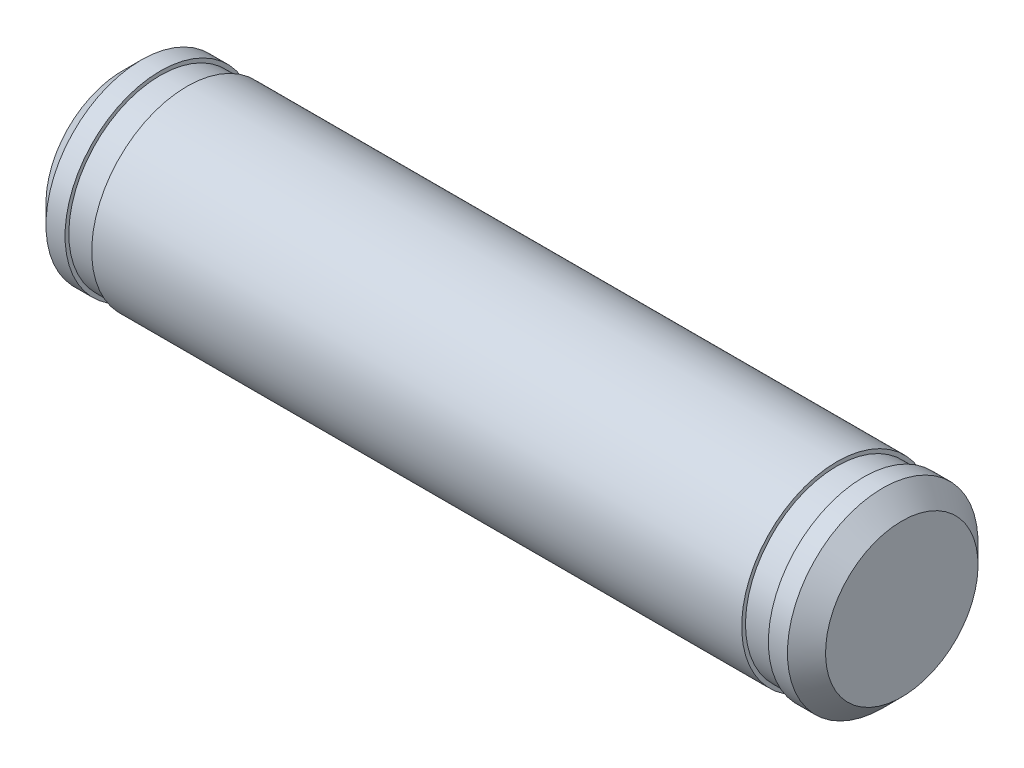
SolidWorks part; units mm, degrees
ref_plane "前视基准面" through (0, 0, 0) normal (0, 0, 1) x (1, 0, 0)
ref_plane "上视基准面" through (0, 0, 0) normal (0, 1, 0) x (1, 0, 0)
ref_plane "右视基准面" through (0, 0, 0) normal (1, 0, 0) x (0, 0, -1)
other "Configuration Table"
sketch "草图1" plane through (0, 0, 0) normal (0, 0, 1) x (1, 0, 0)
  line L0 (-0.2254, 0) -> (10.225, 0) construction
  line L1 (10.225, 0) -> (10.225, 2.5)
  line L2 (10.225, 2.5) -> (9.225, 2.5)
  line L3 (9.225, 2.5) -> (9.225, 2.4)
  line L4 (9.225, 2.4) -> (8.525, 2.4)
  line L5 (8.525, 2.4) -> (8.525, 2.5)
  line L6 (8.525, 2.5) -> (-8.525, 2.5)
  line L7 (0, 2.5) -> (0, 0) construction
  line L8 (0.2254, 0) -> (-10.225, 0) construction
  line L9 (-10.225, 0) -> (-10.225, 2.5)
  line L10 (-8.525, 2.4) -> (-8.525, 2.5)
  line L11 (-9.225, 2.4) -> (-8.525, 2.4)
  line L12 (-9.225, 2.5) -> (-9.225, 2.4)
  line L13 (-10.225, 2.5) -> (-9.225, 2.5)
  line L14 (10.225, 0) -> (-10.225, 0)
  line L15 (8.625, 2.4) -> (8.625, 0) construction
  line L16 (-8.625, 2.4) -> (-8.625, 0) construction
  dimension "D1" = 5
  dimension "D2" = 4.8
  dimension "D3" = 0.7
  dimension "D4" = 1
  dimension "D5" = 0.6
  dimension "D6" = 17.25
revolve "旋转1" add sketch "草图1" angle 360 about L14
chamfer "倒角1" distance 0.5 angle 45 2 edges at (10.225, 2.5, 0) (-10.225, 2.5, 0)
ref_plane "基准面1" through (-8.625, 0, 0) normal (-1, 0, 0) x (0, 0, 1)
ref_plane "基准面2" through (8.625, 0, 0) normal (1, 0, 0) x (0, 0, -1)
